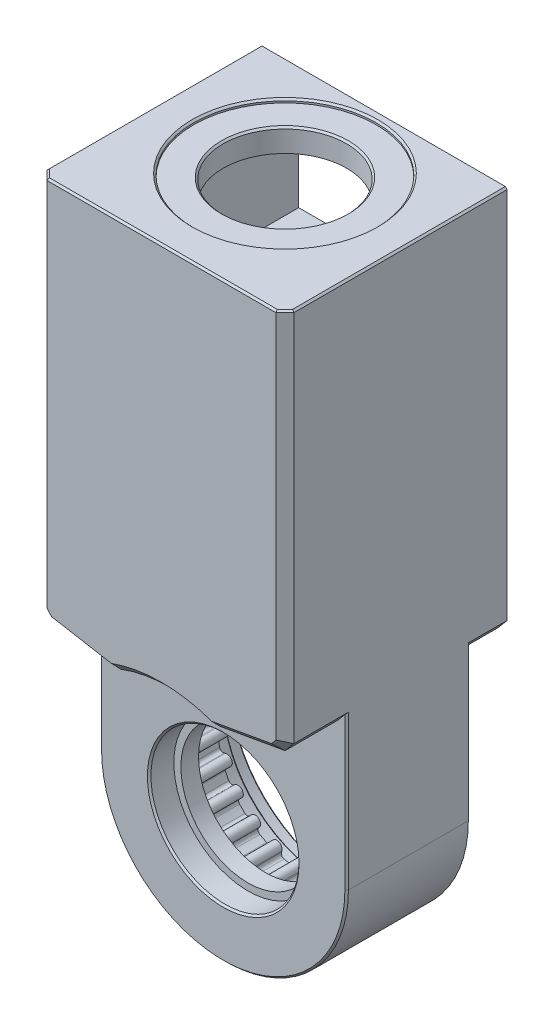
SolidWorks part; units mm, degrees
ref_plane "Ebene vorne" through (0, 0, 0) normal (0, 0, 1) x (1, 0, 0)
ref_plane "Ebene oben" through (0, 0, 0) normal (0, 1, 0) x (1, 0, 0)
ref_plane "Ebene rechts" through (0, 0, 0) normal (1, 0, 0) x (0, 0, -1)
ref_plane "Ebene1" through (0, 0, 0) normal (0, -1, 0) x (1, 0, 0)
sketch "Skizze1" plane through (0, 0, 0) normal (0, -1, 0) x (1, 0, 0)
  line L0 (31.75, 10.3817) -> (0, 10.3817)
  line L1 (0, 10.3817) -> (0, -7.1183)
  line L2 (0, -7.1183) -> (31.75, -7.1183)
  line L3 (31.75, -7.1183) -> (31.75, 10.3817)
  line L4 (0, 10.3817) -> (0, -7.1183) construction
  dimension "D1" = 31.75
  dimension "D2" = 17.5
revolve "Rotation1" add sketch "Skizze1" angle 360 about L4
sketch "Skizze2" plane through (0, 0, 10.3817) normal (0, 0, 1) x (1, 0, 0)
  line L0 (-1.5, 22) -> (-1.5, 23.4521)
  line L1 (1.5, 22) -> (1.5, 23.4521)
  line L2 (5.3718, 21.3868) -> (5.8205, 22.7678)
  line L3 (8.225, 20.4597) -> (8.6737, 21.8407)
  line L4 (11.7178, 18.6801) -> (12.5713, 19.8548)
  line L5 (14.1448, 16.9167) -> (14.9983, 18.0915)
  line L6 (16.9167, 14.1448) -> (18.0915, 14.9983)
  line L7 (18.6801, 11.7178) -> (19.8548, 12.5713)
  line L8 (20.4597, 8.225) -> (21.8407, 8.6737)
  line L9 (21.3868, 5.3718) -> (22.7678, 5.8205)
  line L10 (22, 1.5) -> (23.4521, 1.5)
  line L11 (22, -1.5) -> (23.4521, -1.5)
  line L12 (21.3868, -5.3718) -> (22.7678, -5.8205)
  line L13 (20.4597, -8.225) -> (21.8407, -8.6737)
  line L14 (18.6801, -11.7178) -> (19.8548, -12.5713)
  line L15 (16.9167, -14.1448) -> (18.0915, -14.9983)
  line L16 (14.1448, -16.9167) -> (14.9983, -18.0915)
  line L17 (11.7178, -18.6801) -> (12.5713, -19.8548)
  line L18 (8.225, -20.4597) -> (8.6737, -21.8407)
  line L19 (5.3718, -21.3868) -> (5.8205, -22.7678)
  line L20 (1.5, -22) -> (1.5, -23.4521)
  line L21 (-1.5, -22) -> (-1.5, -23.4521)
  line L22 (-5.3718, -21.3868) -> (-5.8205, -22.7678)
  line L23 (-8.225, -20.4597) -> (-8.6737, -21.8407)
  line L24 (-11.7178, -18.6801) -> (-12.5713, -19.8548)
  line L25 (-14.1448, -16.9167) -> (-14.9983, -18.0915)
  line L26 (-16.9167, -14.1448) -> (-18.0915, -14.9983)
  line L27 (-18.6801, -11.7178) -> (-19.8548, -12.5713)
  line L28 (-20.4597, -8.225) -> (-21.8407, -8.6737)
  line L29 (-21.3868, -5.3718) -> (-22.7678, -5.8205)
  line L30 (-22, -1.5) -> (-23.4521, -1.5)
  line L31 (-22, 1.5) -> (-23.4521, 1.5)
  line L32 (-21.3868, 5.3718) -> (-22.7678, 5.8205)
  line L33 (-20.4597, 8.225) -> (-21.8407, 8.6737)
  line L34 (-18.6801, 11.7178) -> (-19.8548, 12.5713)
  line L35 (-16.9167, 14.1448) -> (-18.0915, 14.9983)
  line L36 (-14.1448, 16.9167) -> (-14.9983, 18.0915)
  line L37 (-11.7178, 18.6801) -> (-12.5713, 19.8548)
  line L38 (-8.225, 20.4597) -> (-8.6737, 21.8407)
  line L39 (-5.3718, 21.3868) -> (-5.8205, 22.7678)
  circle A0 centre (0, 22) radius 1.5
  circle A1 centre (0, 0) radius 23.5
  circle A2 centre (6.7984, 20.9232) radius 1.5
  circle A3 centre (12.9313, 17.7984) radius 1.5
  circle A4 centre (17.7984, 12.9313) radius 1.5
  circle A5 centre (20.9232, 6.7984) radius 1.5
  circle A6 centre (22, 0) radius 1.5
  circle A7 centre (20.9232, -6.7984) radius 1.5
  circle A8 centre (17.7984, -12.9313) radius 1.5
  circle A9 centre (12.9313, -17.7984) radius 1.5
  circle A10 centre (6.7984, -20.9232) radius 1.5
  circle A11 centre (0, -22) radius 1.5
  circle A12 centre (-6.7984, -20.9232) radius 1.5
  circle A13 centre (-12.9313, -17.7984) radius 1.5
  circle A14 centre (-17.7984, -12.9313) radius 1.5
  circle A15 centre (-20.9232, -6.7984) radius 1.5
  circle A16 centre (-22, 0) radius 1.5
  circle A17 centre (-20.9232, 6.7984) radius 1.5
  circle A18 centre (-17.7984, 12.9313) radius 1.5
  circle A19 centre (-12.9313, 17.7984) radius 1.5
  circle A20 centre (-6.7984, 20.9232) radius 1.5
  dimension "D1" = 3
  dimension "D3" = 20
  dimension "D2" = 22
extrude "Schnitt-Linear austragen1" cut sketch "Skizze2" against normal through all contours A20 L38 A1 L37 A19 L36 L35 A18 L34 L33 A17 L32 L31 A16 L30 L29 A15 L28 L27 A14 L26 L25 A13 L24 L23 A12 L22 L21 A11 L20 L19 A10 L18 L17 A9 L16 L15 A8 L14
sketch "Skizze3" plane through (0, 0, 0) normal (0, 1, 0) x (1, 0, 0)
  line L0 (29, 7.1183) -> (0, 7.1183)
  line L1 (0, 7.1183) -> (0, -0.3817)
  line L2 (0, -0.3817) -> (26.5, -0.3817)
  line L3 (26.5, -0.3817) -> (27, 0.1183)
  line L4 (27, 0.1183) -> (29, 0.1183)
  line L5 (29, 0.1183) -> (29, 7.1183)
  line L6 (0, 7.1183) -> (0, -0.3817) construction
  line L7 (31.75, 7.1183) -> (-31.75, 7.1183) construction
  dimension "D1" = 29
  dimension "D2" = 7
  dimension "D3" = 2
  dimension "D4" = 0.5
  dimension "D5" = 45
revolve "Schnitt-Rotation1" cut sketch "Skizze3" angle 360 about L6
fillet "Verrundung1" radius 1 40 edges at (-5.8205, 22.7678, 5.3817) (1.5, 23.4521, 5.3817) (5.8205, 22.7678, 5.3817) (8.6737, 21.8407, 5.3817) (12.5713, 19.8548, 5.3817) (14.9983, 18.0915, 5.3817) (18.0915, 14.9983, 5.3817) (19.8548, 12.5713, 5.3817) (21.8407, 8.6737, 5.3817) (22.7678, 5.8205, 5.3817) (23.4521, 1.5, 5.3817) (23.4521, -1.5, 5.3817) (22.7678, -5.8205, 5.3817) (21.8407, -8.6737, 5.3817) (19.8548, -12.5713, 5.3817) (18.0915, -14.9983, 5.3817) (14.9983, -18.0915, 5.3817) (12.5713, -19.8548, 5.3817) (8.6737, -21.8407, 5.3817) (5.8205, -22.7678, 5.3817) (1.5, -23.4521, 5.3817) (-1.5, -23.4521, 5.3817) (-5.8205, -22.7678, 5.3817) (-8.6737, -21.8407, 5.3817) (-12.5713, -19.8548, 5.3817) (-14.9983, -18.0915, 5.3817) (-18.0915, -14.9983, 5.3817) (-19.8548, -12.5713, 5.3817) (-21.8407, -8.6737, 5.3817) (-22.7678, -5.8205, 5.3817) (-23.4521, -1.5, 5.3817) (-23.4521, 1.5, 5.3817) (-22.7678, 5.8205, 5.3817) (-21.8407, 8.6737, 5.3817) (-19.8548, 12.5713, 5.3817) (-18.0915, 14.9983, 5.3817) (-14.9983, 18.0915, 5.3817) (-12.5713, 19.8548, 5.3817) (-8.6737, 21.8407, 5.3817) (-1.5, 23.4521, 5.3817)
sketch "Skizze13" plane through (0, 0, 10.3817) normal (0, 0, 1) x (1, 0, 0)
  circle A1 centre (0, 0) radius 31.75
  circle A162 centre (0, 0) radius 21
  dimension "D1" = 42
extrude "Aufsatz-Linear austragen1" add sketch "Skizze13" along normal blind 12
sketch "Skizze14" plane through (0, 0, 10.3817) normal (0, 0, -1) x (-1, 0, 0)
  circle A0 centre (0, 0) radius 19
  circle A1 centre (0, 0) radius 21
  dimension "D1" = 38
extrude "Aufsatz-Linear austragen2" add sketch "Skizze14" against normal offset from surface (5 mm away) 7
sketch "Sketch3" plane through (0, 0, -7.1183) normal (0, 0, -1) x (-1, 0, 0)
  circle A0 centre (0, 0) radius 31.75
  circle A1 centre (0, 0) radius 32.75
  circle M3 centre (0, 0) radius 31.75
  dimension "D1" = 65.5
extrude "Boss-Extrude2" add sketch "Sketch3" against normal through all contours A1 M3 | A0
sketch "Sketch4" plane through (0, 0, -7.1183) normal (0, 0, -1) x (-1, 0, 0)
  line L1 (-35, 0) -> (35, 0)
  line L2 (-35, 0) -> (-35, 150)
  line L3 (-35, 150) -> (35, 150)
  line L4 (35, 0) -> (35, 150)
  line L5 (-35, 0) -> (35, 150) construction
  line L6 (-35, 150) -> (35, 0) construction
  circle A0 centre (0, 0) radius 32.75
  circle A1 centre (0, 0) radius 35
  point P8 (0, 75)
  circle M2 centre (0, 0) radius 32.75
  dimension "D1" = 70
  dimension "D2" = 150
extrude "Boss-Extrude3" add sketch "Sketch4" along normal blind 5.5 and the other way through all contours A1 M2 | L1 A1 M2 | A1 L4 L3 L2
sketch "Sketch5" plane through (0, 0, -12.6183) normal (0, 0, -1) x (-1, 0, 0)
  line L0 (-14.0026, 37.469) -> (-32.538, 40.7373)
  line L1 (-35, -35) -> (35, -35)
  line L2 (-35, -35) -> (-35, 35)
  line L3 (-35, 35) -> (35, 35)
  line L4 (35, -35) -> (35, 35)
  line L5 (-35, -35) -> (35, 35) construction
  line L6 (-35, 35) -> (35, -35) construction
  line L7 (35, 0) -> (35, 150) construction
  line L8 (-35, 41.1714) -> (0, 35) construction
  line L9 (-35, 150) -> (35, 150)
  line L10 (-35, 150) -> (-35, 43.6714)
  line L11 (-34.5, 35) -> (35, 35)
  line L12 (35, 150) -> (35, 43.6714)
  line L13 (-35, 150) -> (35, 35) construction
  line L14 (-34.5, 35) -> (35, 150) construction
  line L15 (0, 35) -> (0, 47.057) construction
  line L16 (14.0026, 37.469) -> (32.538, 40.7373)
  line L17 (-32.538, 40.7373) -> (-35, 43.6714)
  line L18 (32.538, 40.7373) -> (35, 43.6714)
  arc A0 (-35, 19.3649) -> (35, 19.3649) centre (0, 0) ccw
  arc A1 (19.3649, 35) -> (-19.3649, 35) centre (0, 0) ccw
  point P13 (0.1254, 92.2939)
  point P21 (35, 41.1714)
  line M11 (35, 0) -> (35, 150)
  line M12 (35, 150) -> (-35, 150)
  line M13 (-35, 150) -> (-35, 0)
  dimension "D1" = 80
  dimension "D2" = 70
  dimension "D3" = 10
extrude "Boss-Extrude4" add sketch "Sketch5" along normal blind 17.5 and the other way offset from surface (52.5 mm away) 17.5 contours A1 L3 M11 M12 M13
ref_plane "Plane1" through (0, 0, 4.8817) normal (0, 0, 1) x (1, 0, 0)
sketch "Sketch7" plane through (0, 0, 4.8817) normal (0, 0, -1) x (-1, 0, 0)
  line L0 (0, 150) -> (0, 0) construction
  line L1 (35, 150) -> (-35, 150) construction
  line L3 (-23.6, 45) -> (23.6, 45)
  line L4 (-23.6, 45) -> (-23.6, 106)
  line L5 (-23.6, 106) -> (23.6, 106)
  line L6 (23.6, 45) -> (23.6, 106)
  line L7 (-23.6, 45) -> (23.6, 106) construction
  line L8 (-23.6, 106) -> (23.6, 45) construction
  line L9 (-11.1, 106) -> (11.1, 106)
  line L10 (-11.1, 106) -> (-11.1, 116)
  line L11 (-11.1, 116) -> (11.1, 116)
  line L12 (11.1, 106) -> (11.1, 116)
  line L13 (-11.1, 106) -> (11.1, 116) construction
  line L14 (-11.1, 116) -> (11.1, 106) construction
  line L15 (-23.6, 140) -> (23.6, 140)
  line L16 (-23.6, 140) -> (-23.6, 116)
  line L17 (-23.6, 116) -> (23.6, 116)
  line L18 (23.6, 140) -> (23.6, 116)
  line L19 (-23.6, 140) -> (23.6, 116) construction
  line L20 (-23.6, 116) -> (23.6, 140) construction
  point P5 (0, 75.5)
  point P14 (0, 111)
  point P16 (0, 128)
  dimension "D1" = 61
  dimension "D2" = 47.2
  dimension "D3" = 45
  dimension "D4" = 10
  dimension "D5" = 22.2
  dimension "D6" = 10
extrude "Cut-Extrude2" cut sketch "Sketch7" along normal through all and the other way blind 23.6 contours L6 L3 L4 L5 | L12 L5 L10 L11 | L15 L18 L17 L11 L16
sketch "Sketch10" plane through (0, 0, 4.8817) normal (0, 0, 1) x (1, 0, 0)
  line L0 (0, 150) -> (0, 0) construction
  line L1 (-35, 150) -> (35, 150) construction
  line L2 (25.85, 150) -> (0, 150)
  line L3 (17.5, 149) -> (17.5, 142.5)
  line L4 (17.5, 142.5) -> (19.5, 142.5)
  line L5 (21, 142) -> (21, 140)
  line L6 (23.6, 140) -> (-23.6, 140) construction
  line L7 (23.6, 140) -> (-23.6, 140)
  line L8 (21, 142) -> (19.5, 142)
  line L9 (19.5, 142) -> (19.5, 142.5)
  line L12 (17.5, 149) -> (25.85, 149)
  line L13 (25.85, 149) -> (25.85, 150)
  dimension "D2" = 42
  dimension "D3" = 2
  dimension "D4" = 0.5
  dimension "D5" = 39
  dimension "D6" = 51.7
  dimension "D7" = 1
revolve "Cut-Revolve1" cut sketch "Sketch10" angle 360 about L0
sketch "Sketch11" plane through (0, 0, -30.1183) normal (0, 0, -1) x (-1, 0, 0)
  line L5 (14.0026, 37.469) -> (32.538, 40.7373)
  line L6 (35, 43.6714) -> (35, 150)
  line L7 (35, 150) -> (-35, 150)
  line L8 (-35, 150) -> (-35, 43.6714)
  line L9 (-32.538, 40.7373) -> (-14.0026, 37.469)
  line L10 (14.0026, 37.469) -> (32.538, 40.7373)
  line L11 (35, 43.6714) -> (35, 150)
  line L12 (35, 150) -> (-35, 150)
  line L13 (-35, 150) -> (-35, 43.6714)
  line L14 (-32.538, 40.7373) -> (-14.0026, 37.469)
  line L17 (32.538, 40.7373) -> (35, 43.6714)
  line L18 (32.538, 40.7373) -> (35, 43.6714)
  line L19 (-35, 43.6714) -> (-32.538, 40.7373)
  line L20 (-35, 43.6714) -> (-32.538, 40.7373)
  arc A1 (14.0026, 37.469) -> (-14.0026, 37.469) centre (0, 0) ccw
  arc A2 (14.0026, 37.469) -> (-14.0026, 37.469) centre (0, 0) ccw
  dimension "D1" = 0
extrude "Cut-Extrude3" cut sketch "Sketch11" against normal blind 7
chamfer "2,5mm Chamfer1" distance 2.5 angle 45 7 edges at (35, 96.8357, 39.8817) (0, 40, 39.8817) (-35, 96.8357, 39.8817) (23.2703, 39.1032, 39.8817) (-23.2703, 39.1032, 39.8817) (33.769, 42.2044, 39.8817) (-33.769, 42.2044, 39.8817)
chamfer "0,5mm Chamfer2" distance 0.5 angle 45 33 edges at (33.75, 150, 38.6317) (0, 150, 39.8817) (-33.75, 150, 38.6317) (-35, 150, 7.1317) (35, 150, 7.1317) (-25.85, 150, 4.8817) (11.1, 106, 2.6817) (11.1, 116, 2.6817) (-11.1, 116, 2.6817) (-11.1, 106, 2.6817) (-17.5, 149, 4.8817) (-21, 140, 4.8817) (29, 0, -7.1183) (-35, 21.8357, 22.3817) (0, -35, 22.3817) (35, 21.8357, 22.3817) (21, 0, 22.3817) (35, 21.8357, -12.6183) (0, -35, -12.6183) (-35, 21.8357, -12.6183) (-32.75, 0, -12.6183) (-23.6, 75.5, -23.1183) (0, 45, -23.1183) (23.6, 75.5, -23.1183) (17.35, 106, -23.1183) (11.1, 111, -23.1183) (17.35, 116, -23.1183) (23.6, 128, -23.1183) (0, 140, -23.1183) (-23.6, 128, -23.1183) (-17.35, 116, -23.1183) (-11.1, 111, -23.1183) (-17.35, 106, -23.1183)
